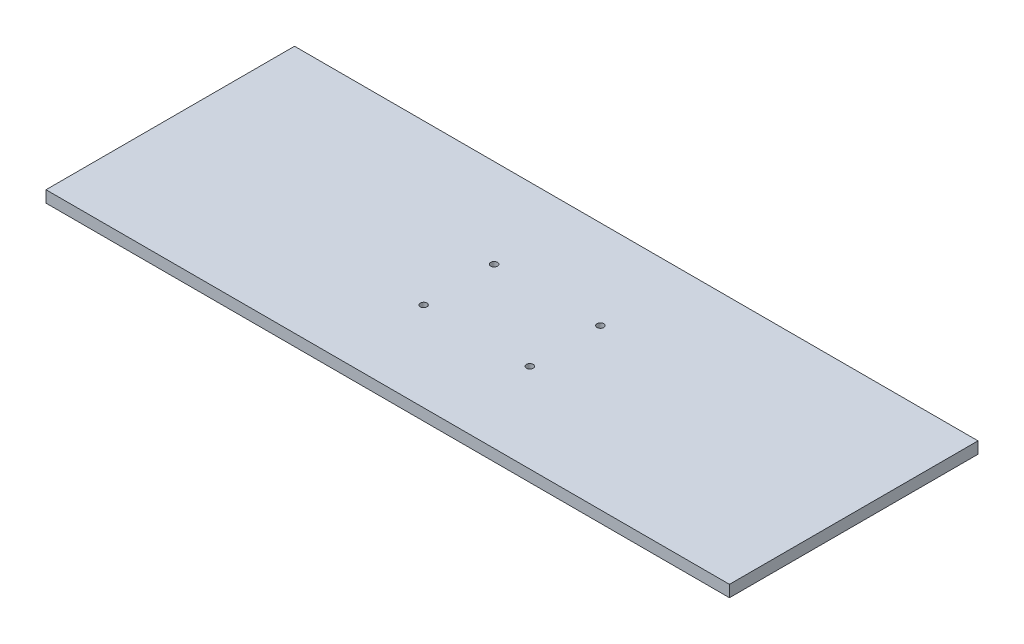
SolidWorks part; units mm, degrees
ref_plane "Front Plane" through (0, 0, 0) normal (0, 0, 1) x (1, 0, 0)
ref_plane "Top Plane" through (0, 0, 0) normal (0, 1, 0) x (1, 0, 0)
ref_plane "Right Plane" through (0, 0, 0) normal (1, 0, 0) x (0, 0, -1)
sketch "Sketch1" plane through (0, 0, 0) normal (0, 1, 0) x (1, 0, 0)
  line L1 (0, 0) -> (558.8, 0)
  line L2 (0, 0) -> (0, 203.2)
  line L3 (0, 203.2) -> (558.8, 203.2)
  line L4 (558.8, 0) -> (558.8, 203.2)
  line L5 (279.4, 203.2) -> (279.4, 0) construction
  line L6 (0, 101.6) -> (558.8, 101.6) construction
  point P124 (279.4, 101.6)
  dimension "D1" = 558.8
  dimension "D2" = 203.2
extrude "Table Blank" add sketch "Sketch1" along normal blind 9.525
sketch "Table Location" plane through (0, 9.525, 0) normal (0, 1, 0) x (1, 0, 0)
  line L0 (0, 101.6) -> (558.8, 101.6) construction
  line L1 (203.2, 152.4) -> (355.6, 152.4) construction
  line L2 (203.2, 152.4) -> (203.2, 50.8) construction
  line L3 (203.2, 50.8) -> (355.6, 50.8) construction
  line L4 (355.6, 152.4) -> (355.6, 50.8) construction
  line L5 (279.4, 50.8) -> (279.4, 152.4) construction
  line L6 (203.2, 101.6) -> (355.6, 101.6) construction
  line L7 (279.4, 203.2) -> (279.4, 0) construction
  line L9 (235.966, 130.429) -> (322.834, 130.429) construction
  line L10 (235.966, 130.429) -> (235.966, 72.771) construction
  line L11 (235.966, 72.771) -> (322.834, 72.771) construction
  line L12 (322.834, 130.429) -> (322.834, 72.771) construction
  line L13 (279.4, 72.771) -> (279.4, 130.429) construction
  line L14 (235.966, 101.6) -> (322.834, 101.6) construction
  circle A0 centre (235.966, 72.771) radius 2.5 construction
  circle A1 centre (235.966, 130.429) radius 2.5 construction
  circle A2 centre (322.834, 130.429) radius 2.5 construction
  circle A3 centre (322.834, 72.771) radius 2.5 construction
  point P124 (279.4, 101.6)
  point P224 (279.4, 101.6)
  dimension "D5" = 5
  dimension "D1" = 152.4
  dimension "D2" = 101.6
  dimension "D3" = 86.868
  dimension "D4" = 57.658
hole_wizard "Table Holes (M5 Clearance)" positions "Sketch4" profile "Sketch5" hole size "M5" standard "ANSI Metric" end condition through all
sketch "Sketch4" plane through (0, 9.525, 0) normal (0, 1, 0) x (1, 0, 0)
  point P0 (235.966, 130.429)
  point P3 (322.834, 130.429)
  point P6 (322.834, 72.771)
  point P9 (235.966, 72.771)
sketch "Sketch5" plane through (235.966, 9.525, -130.429) normal (1, 0, 0) x (0, 0, 1)
  line L0 (0, 0) -> (0, 9.525)
  line L1 (0, 9.525) -> (2.75, 9.525)
  line L2 (2.75, 9.525) -> (2.75, 0)
  line L5 (2.75, 0) -> (0, 0)
  line L11 (0, -6.35) -> (0, 107.95) construction
  dimension "Thru Hole Dia." = 5.5
  dimension "Thru Hole Depth" = 9.525
equation "\"baseplate x\"= 22"
equation "\"baseplate y\"= 8"
equation "\"D1@Sketch1\"=\"baseplate x\""
equation "\"D2@Sketch1\"=\"baseplate y\""
equation "\"stock thick\"= 3 / 8"
equation "\"D1@Table Blank\" = \"stock thick\""
equation "\"table x\"= 6"
equation "\"table y\"= 4"
equation "\"D1@Table Location\" = \"table x\""
equation "\"D2@Table Location\" = \"table y\""
